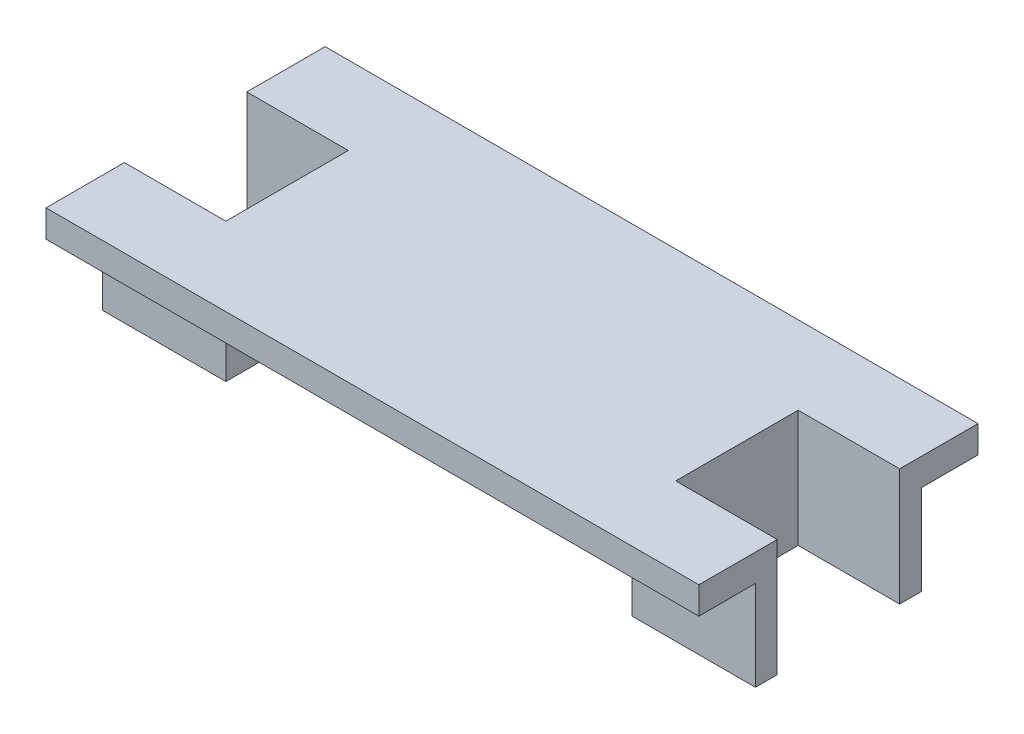
SolidWorks part; units mm, degrees
ref_plane "Front Plane" through (0, 0, 0) normal (0, 0, 1) x (1, 0, 0)
ref_plane "Top Plane" through (0, 0, 0) normal (0, 1, 0) x (1, 0, 0)
ref_plane "Right Plane" through (0, 0, 0) normal (1, 0, 0) x (0, 0, -1)
sketch "Sketch1" plane through (0, 0, 0) normal (0, 1, 0) x (1, 0, 0)
  line L0 (-60, 25.6535) -> (-60, 11.2497)
  line L1 (-60, 25.6535) -> (60, 25.6535)
  line L3 (-60, -25.6535) -> (60, -25.6535)
  line L5 (-60, 25.6535) -> (60, -25.6535) construction
  line L6 (-60, -25.6535) -> (60, 25.6535) construction
  line L7 (-60, 11.2497) -> (-41.343, 11.2497)
  line L8 (-41.343, 11.2497) -> (-41.343, -11.2498)
  line L9 (-41.343, -11.2498) -> (-60, -11.2498)
  line L10 (-60, -11.2498) -> (-60, -25.6535)
  line L11 (60, 25.6535) -> (60, 11.2535)
  line L12 (60, 11.2535) -> (41.343, 11.2535)
  line L13 (41.343, 11.2535) -> (41.343, -11.2535)
  line L14 (41.343, -11.2535) -> (60, -11.2535)
  line L15 (60, -11.2535) -> (60, -25.6535)
  point P0 (0, 0)
  dimension "D1" = 120
  dimension "D2" = 51.307
  dimension "D3" = 14.4038
  dimension "D4" = 14.4038
  dimension "D5" = 18.657
  dimension "D6" = 18.657
  dimension "D7" = 14.4
  dimension "D8" = 14.4
extrude "Boss-Extrude1" add sketch "Sketch1" along normal blind 5
sketch "Sketch2" plane through (0, 0, 0) normal (0, -1, 0) x (1, 0, 0)
  line L0 (60, 15.2535) -> (37.343, 15.2535)
  line L1 (60, 25.6535) -> (60, 11.2535) construction
  line L2 (37.343, 15.2535) -> (37.343, -15.2535)
  line L3 (37.343, -15.2535) -> (60, -15.2535)
  line L4 (60, -11.2535) -> (60, -25.6535) construction
  line L5 (60, -15.2535) -> (60, -11.2535)
  line L6 (60, -11.2535) -> (41.343, -11.2535)
  line L7 (41.343, -11.2535) -> (41.343, 11.2535)
  line L8 (41.343, 11.2535) -> (60, 11.2535)
  line L9 (60, 11.2535) -> (60, 15.2535)
  line L10 (-60, 11.2498) -> (-60, 15.2498)
  line L11 (-60, 11.2498) -> (-60, 25.6535) construction
  line L12 (-60, 15.2498) -> (-37.343, 15.2498)
  line L13 (-37.343, 15.2498) -> (-37.343, -15.2535)
  line L14 (-37.343, -15.2535) -> (-60, -15.2535)
  line L15 (-60, -25.6535) -> (-60, -11.2497) construction
  line L16 (-60, -15.2535) -> (-60, -11.2497)
  line L17 (-60, -11.2497) -> (-41.343, -11.2497)
  line L18 (-41.343, -11.2497) -> (-41.343, 11.2498)
  line L19 (-41.343, 11.2498) -> (-60, 11.2498)
  dimension "D1" = 4
  dimension "D2" = 4
  dimension "D3" = 4
  dimension "D4" = 4
  dimension "D5" = 4.0038
  dimension "D6" = 4
extrude "Boss-Extrude2" add sketch "Sketch2" along normal blind 16.532
